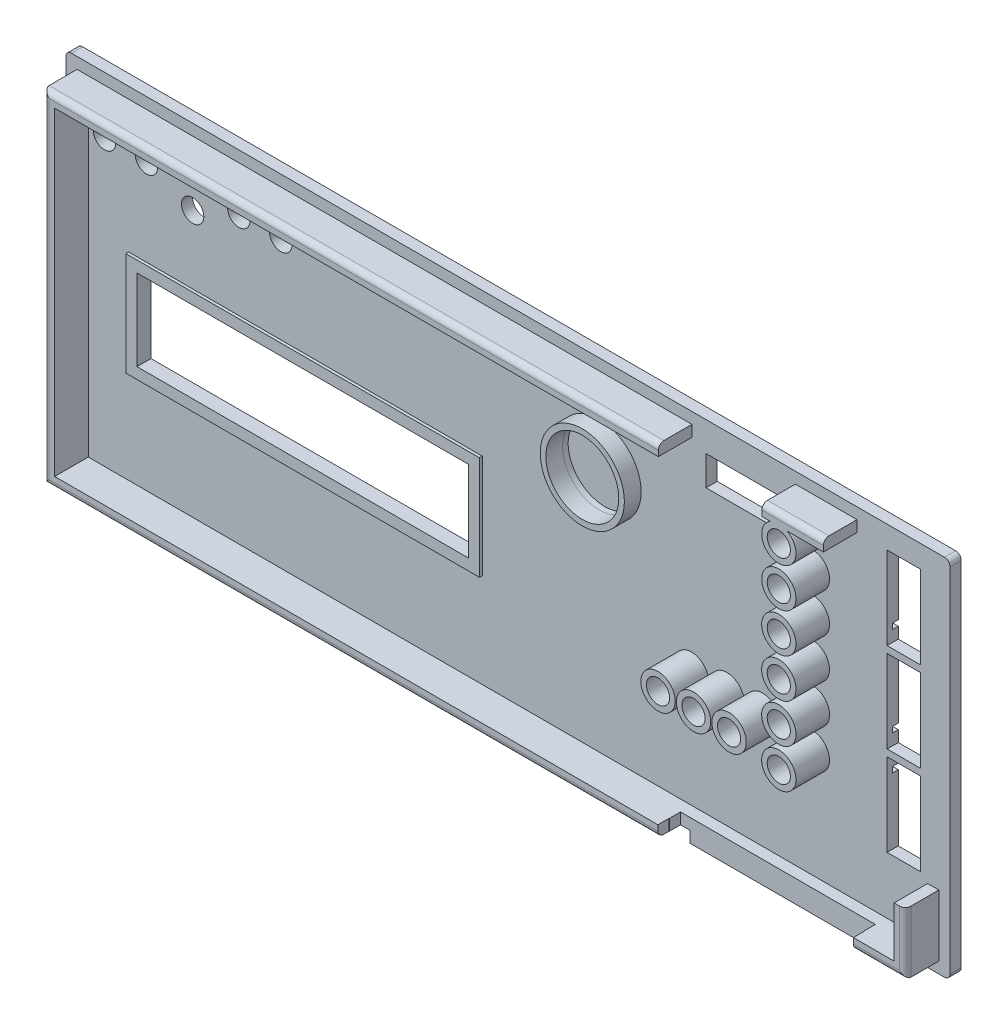
SolidWorks part; units mm, degrees
material "ABS"
ref_plane "Plano frontal" through (0, 0, 0) normal (0, 0, 1) x (1, 0, 0)
ref_plane "Plano superior" through (0, 0, 0) normal (0, 1, 0) x (1, 0, 0)
ref_plane "Plano direito" through (0, 0, 0) normal (1, 0, 0) x (0, 0, -1)
sketch "Esboço1" plane through (0, 0, 0) normal (0, 0, 1) x (1, 0, 0)
  line L1 (0, 0) -> (-158, 0)
  line L2 (0, 0) -> (0, 65)
  line L3 (0, 65) -> (-158, 65)
  line L4 (-158, 0) -> (-158, 65)
  dimension "D1" = 158
  dimension "D2" = 65
extrude "Ressalto-extrusão1" add sketch "Esboço1" along normal blind 2
sketch "Esboço3" [suppressed] plane through (0, 0, 0) normal (0, -1, 0) x (-1, 0, 0)
  line L0 (14.5726, -4) -> (14.5726, -2)
  line L1 (158, -2) -> (0, -2) construction
  line L2 (14.5726, -2) -> (44.0726, -2)
  line L3 (44.0726, -2) -> (44.0726, -4)
  line L4 (44.0726, -4) -> (44.0726, -7.5976)
  line L5 (40.5726, -7.0976) -> (40.5726, -7.5976)
  line L6 (40.5726, -7.0976) -> (40.5726, -8.82) construction
  line L7 (40.5726, -7.5976) -> (41.0832, -7.5976)
  line L8 (43.5621, -7.5976) -> (44.0726, -7.5976)
  line L9 (40.5726, -7.0976) -> (38.2226, -7.0976)
  line L10 (38.2226, -7.0976) -> (38.2226, -6.57)
  line L11 (20.4226, -7.0904) -> (18.0726, -7.0904)
  line L12 (18.0726, -7.0904) -> (18.0726, -7.8318)
  line L13 (36.3225, -4.67) -> (22.3225, -4.6704)
  line L14 (20.4226, -6.5705) -> (20.4226, -7.0904)
  line L15 (18.0726, -8.82) -> (18.0726, -7.0904) construction
  line L16 (18.0726, -7.8318) -> (17.7669, -7.8318)
  line L17 (14.5726, -4) -> (14.5726, -8.82) construction
  line L18 (14.5726, -7.8318) -> (14.5726, -4)
  line L19 (14.8783, -7.8318) -> (14.5726, -7.8318)
  arc A0 (17.7669, -7.8318) -> (14.8783, -7.8318) centre (16.3226, -8.82) ccw
  arc A3 (43.5621, -7.5976) -> (41.0832, -7.5976) centre (42.3226, -8.833) ccw
  arc A5 (38.2226, -6.57) -> (36.3225, -4.67) centre (36.3226, -6.57) ccw
  arc A6 (22.3225, -4.6704) -> (20.4226, -6.5705) centre (22.3226, -6.5704) ccw
  dimension "D1" = 0.5
sketch "Esboço4" plane through (0, 0, 2) normal (0, 0, 1) x (1, 0, 0)
  line L0 (-156, 2) -> (-2, 2)
  line L1 (-2, 2) -> (-2, 63)
  line L2 (-2, 63) -> (-156, 63)
  line L3 (-156, 63) -> (-156, 2)
  line L4 (-154, 4) -> (-4, 4)
  line L5 (-4, 4) -> (-4, 61)
  line L6 (-4, 61) -> (-154, 61)
  line L7 (-154, 61) -> (-154, 4)
  dimension "D1" = 2
extrude "Ressalto-extrusão3" add sketch "Esboço4" along normal blind 6
sketch "Esboço5" plane through (0, 0, 8) normal (0, 0, 1) x (1, 0, 0)
  line L0 (-156, 2) -> (-2, 2) construction
  line L1 (-46.2005, 2) -> (-11.2842, 2)
  line L2 (-46.2005, 2) -> (-46.2005, 4)
  line L3 (-46.2005, 4) -> (-11.2842, 4)
  line L4 (-11.2842, 2) -> (-11.2842, 4)
  line L5 (-154, 4) -> (-4, 4) construction
extrude "Corte-extrusão1" cut sketch "Esboço5" against normal blind 2
sketch "Esboço6" plane through (0, 0, 0) normal (0, 0, -1) x (-1, 0, 0)
  line L1 (11.25, 61) -> (5.25, 61)
  line L2 (11.25, 61) -> (11.25, 46.2)
  line L3 (11.25, 46.2) -> (5.25, 46.2)
  line L4 (5.25, 61) -> (5.25, 46.2)
  line L5 (28.6082, 54.44) -> (43.6082, 54.44)
  line L6 (28.6082, 54.44) -> (28.6082, 59.75)
  line L7 (0, 65) -> (158, 65) construction
  line L8 (0, 0) -> (0, 65) construction
  line L9 (11.25, 45) -> (5.25, 45)
  line L10 (11.25, 45) -> (11.25, 30.2)
  line L11 (11.25, 30.2) -> (5.25, 30.2)
  line L12 (5.25, 45) -> (5.25, 30.2)
  line L13 (11.25, 29) -> (5.25, 29)
  line L14 (11.25, 29) -> (11.25, 14.2)
  line L15 (11.25, 14.2) -> (5.25, 14.2)
  line L16 (5.25, 29) -> (5.25, 14.2)
  line L17 (28.6082, 59.75) -> (43.6082, 59.75)
  line L18 (43.6082, 54.44) -> (43.6082, 59.75)
  dimension "D1" = 6
  dimension "D2" = 4
  dimension "D3" = 14.8
  dimension "D4" = 5.25
  dimension "D6" = 1.2
  dimension "D5" = 3
extrude "Corte-extrusão2" cut sketch "Esboço6" against normal blind 4
fillet "Filete2" radius 1 4 edges at (-158, 0, 1) (-158, 65, 1) (0, 0, 1) (0, 65, 1)
sketch "Esboço7" plane through (0, 0, 0) normal (0, 0, -1) x (-1, 0, 0)
  line L0 (87.0918, 25.05) -> (87.0918, 25.7) construction
  line L1 (85.5918, 22.85) -> (144.7918, 22.85)
  line L2 (85.5918, 22.85) -> (85.5918, 37.35)
  line L3 (85.5918, 37.35) -> (144.7918, 37.35)
  line L4 (144.7918, 22.85) -> (144.7918, 37.35)
  line L5 (95.3418, 24.35) -> (94.7918, 24.35) construction
  line L7 (143.2918, 29.9) -> (143.2918, 29.25) construction
  point P6 (87.0918, 25.375)
  point P9 (95.0668, 24.35)
  dimension "D1" = 14.5
  dimension "D2" = 1.5
  dimension "D3" = 1.5
  dimension "D4" = 1.5
extrude "Corte-extrusão3" cut sketch "Esboço7" against normal blind 2
sketch "Esboço8" plane through (0, 0, 2) normal (0, 0, 1) x (1, 0, 0)
  line L0 (-83.5918, 20.85) -> (-83.5918, 39.35)
  line L1 (-85.5918, 22.85) -> (-144.7918, 22.85)
  line L2 (-85.5918, 22.85) -> (-85.5918, 37.35)
  line L3 (-85.5918, 37.35) -> (-144.7918, 37.35)
  line L4 (-144.7918, 22.85) -> (-144.7918, 37.35)
  line L5 (-83.5918, 39.35) -> (-146.7918, 39.35)
  line L6 (-146.7918, 20.85) -> (-146.7918, 39.35)
  line L7 (-83.5918, 20.85) -> (-146.7918, 20.85)
  dimension "D1" = 2
extrude "Ressalto-extrusão4" add sketch "Esboço8" along normal blind 0.5
sketch "Esboço9" plane through (0, 0, 2) normal (0, 0, 1) x (1, 0, 0)
  line L1 (-1, 65) -> (-157, 65) construction
  line L2 (-158, 64) -> (-158, 1) construction
  circle A0 centre (-119.6, 55) radius 2
  circle A1 centre (-127.1, 55) radius 2
  circle A2 centre (-135.35, 58.5) radius 2
  circle A3 centre (-143.6, 55) radius 2
  circle A4 centre (-135.35, 51.5) radius 2
  circle A5 centre (-151.1, 55) radius 2
  dimension "D1" = 4
  dimension "D2" = 4
  dimension "D3" = 4
  dimension "D4" = 4
  dimension "D5" = 4
  dimension "D6" = 4
  dimension "D7" = 7.5
  dimension "D8" = 7.5
  dimension "D9" = 10
  dimension "D10" = 16.5
  dimension "D11" = 6.9
  dimension "D12" = 7
  dimension "D13" = 3.5
  dimension "D14" = 8.25
sketch "Esboço12" plane through (0, 0, 2) normal (0, 0, 1) x (1, 0, 0)
  circle A0 centre (-46.1882, 24.665) radius 1.87
  circle A1 centre (-39.8382, 24.665) radius 1.87
  circle A2 centre (-33.4882, 24.665) radius 1.87
  circle A3 centre (-24.5982, 23.32) radius 1.87
  circle A4 centre (-24.5982, 30.32) radius 1.87
  circle A5 centre (-24.5982, 37.32) radius 1.87
  circle A6 centre (-24.5982, 44.32) radius 1.87
  circle A7 centre (-24.5982, 51.32) radius 1.87
  circle A8 centre (-24.5982, 58.32) radius 1.87
  circle A9 centre (-46.1882, 24.665) radius 2.07
  circle A10 centre (-39.8382, 24.665) radius 2.07
  circle A11 centre (-33.4882, 24.665) radius 2.07
  circle A12 centre (-24.5982, 23.32) radius 2.07
  circle A13 centre (-24.5982, 30.32) radius 2.07
  circle A14 centre (-24.5982, 37.32) radius 2.07
  circle A15 centre (-24.5982, 44.32) radius 2.07
  circle A16 centre (-24.5982, 51.32) radius 2.07
  circle A17 centre (-24.5982, 58.32) radius 2.07
  circle A18 centre (-24.5982, 23.32) radius 3.07
  circle A19 centre (-33.4882, 24.665) radius 3.07
  circle A20 centre (-39.8382, 24.665) radius 3.07
  circle A21 centre (-46.1882, 24.665) radius 3.07
  circle A22 centre (-24.5982, 30.32) radius 3.07
  circle A23 centre (-24.5982, 37.32) radius 3.07
  circle A24 centre (-24.5982, 44.32) radius 3.07
  circle A25 centre (-24.5982, 51.32) radius 3.07
  circle A26 centre (-24.5982, 58.32) radius 3.07
  dimension "D3" = 7
  dimension "D1" = 7
  dimension "D2" = 1
extrude "Ressalto-extrusão7" add sketch "Esboço12" along normal blind 6
sketch "Esboço13" plane through (0, 0, 2) normal (0, 0, 1) x (1, 0, 0)
  circle A1 centre (-24.5982, 58.32) radius 2.07
  circle A2 centre (-24.5982, 58.32) radius 2.07
  circle A3 centre (-24.5982, 51.32) radius 2.07
  circle A4 centre (-24.5982, 51.32) radius 2.07
  circle A5 centre (-24.5982, 44.32) radius 2.07
  circle A6 centre (-24.5982, 44.32) radius 2.07
  circle A7 centre (-24.5982, 37.32) radius 2.07
  circle A8 centre (-24.5982, 37.32) radius 2.07
  circle A9 centre (-24.5982, 30.32) radius 2.07
  circle A10 centre (-24.5982, 30.32) radius 2.07
  circle A11 centre (-24.5982, 23.32) radius 2.07
  circle A12 centre (-24.5982, 23.32) radius 2.07
  circle A13 centre (-33.4882, 24.665) radius 2.07
  circle A14 centre (-33.4882, 24.665) radius 2.07
  circle A15 centre (-39.8382, 24.665) radius 2.07
  circle A16 centre (-39.8382, 24.665) radius 2.07
  circle A17 centre (-46.1882, 24.665) radius 2.07
  circle A18 centre (-46.1882, 24.665) radius 2.07
  dimension "D1" = 0
  dimension "D2" = 0
  dimension "D3" = 0
  dimension "D4" = 0
  dimension "D5" = 0
  dimension "D6" = 0
  dimension "D7" = 0
  dimension "D8" = 0
  dimension "D9" = 0
extrude "Corte-extrusão7" cut sketch "Esboço13" against normal blind 1.5
fillet "Filete8" radius 1 9 edges at (-44.1182, 24.665, 0.5) (-22.5282, 58.32, 0.5) (-22.5282, 51.32, 0.5) (-22.5282, 44.32, 0.5) (-22.5282, 37.32, 0.5) (-22.5282, 30.32, 0.5) (-22.5282, 23.32, 0.5) (-31.4182, 24.665, 0.5) (-37.7682, 24.665, 0.5)
sketch "Esboço15" plane through (0, 0, 2) normal (0, 0, 1) x (1, 0, 0)
  circle A0 centre (-62.7168, 48.007) radius 6.5216
  circle A1 centre (-62.7168, 48.007) radius 7.5216
  dimension "D1" = 1
extrude "Ressalto-extrusão15" add sketch "Esboço15" along normal blind 3 separate body
sketch "Esboço16" plane through (0, 0, 2) normal (0, 0, 1) x (1, 0, 0)
  circle A0 centre (-62.7168, 48.007) radius 6.5216
  circle A1 centre (-62.7168, 48.007) radius 6.5216 construction
fillet "Filete9" radius 1 5 edges at (-101.1002, 2, 8) (-156, 32.5, 8) (-79, 63, 8) (-2, 32.5, 8) (-6.6421, 2, 8)
sketch "Esboço18" plane through (0, 0, 2) normal (0, 0, 1) x (1, 0, 0)
  line L1 (-1.7179, 13.0006) -> (-16.6289, 13.0006)
  line L2 (-1.7179, 13.0006) -> (-1.7179, 63.3344)
  line L3 (-1.7179, 63.3344) -> (-16.6289, 63.3344)
  line L4 (-16.6289, 13.0006) -> (-16.6289, 63.3344)
  line L7 (-11.3413, 11.3001) -> (-46.1715, 11.3001)
  line L8 (-11.3413, 11.3001) -> (-11.3413, 1.1781)
  line L9 (-11.3413, 1.1781) -> (-46.1715, 1.1781)
  line L10 (-46.1715, 11.3001) -> (-46.1715, 1.1781)
  line L11 (-46.1248, 64.7569) -> (-27.6214, 64.7569)
  line L12 (-46.1248, 64.7569) -> (-46.1248, 50.7859)
  line L13 (-46.1248, 50.7859) -> (-27.6214, 50.7859)
  line L14 (-27.6214, 64.7569) -> (-27.6214, 50.7859)
  circle A0 centre (-24.5982, 51.32) radius 3.07 construction
extrude "Corte-extrusão11" cut sketch "Esboço18" along normal blind 12
extrude "Corte-extrusão12" cut sketch "Esboço16" against normal blind 1
extrude "Corte-extrusão13" cut sketch "Esboço9" against normal blind 4
sketch "Esboço19" plane through (0, 0, 2) normal (0, 0, 1) x (1, 0, 0)
  line L1 (-46.1715, 4) -> (-11.3413, 4)
  line L2 (-46.1715, 4) -> (-46.1715, 2)
  line L3 (-46.1715, 2) -> (-11.3413, 2)
  line L4 (-11.3413, 4) -> (-11.3413, 2)
extrude "Ressalto-extrusão16" add sketch "Esboço19" along normal blind 2
sketch "Esboço20" plane through (0, 0, 0) normal (0, 0, -1) x (-1, 0, 0)
  line L0 (11.25, 33.2) -> (17.1926, 33.2)
  line L1 (17.1926, 33.2) -> (17.1926, 37.1)
  line L2 (17.1926, 37.1) -> (16.2335, 37.1)
  line L3 (16.2335, 37.1) -> (13.5902, 35.6872)
  line L4 (11.25, 30.2) -> (11.25, 45) construction
  line L5 (17.1926, 37.1) -> (17.1926, 42)
  line L6 (17.1926, 42) -> (16.2335, 42)
  line L7 (16.2335, 42) -> (13.5902, 40.5872)
  line L8 (5.25, 30.2) -> (11.25, 30.2) construction
  line L9 (11.25, 32.2) -> (18.1926, 32.2)
  line L10 (18.1926, 32.2) -> (18.1926, 37.1)
  line L11 (18.1926, 37.1) -> (18.1926, 43)
  line L12 (18.1926, 43) -> (15.983, 43)
  line L13 (15.983, 43) -> (13.1188, 41.4691)
  line L14 (17.1926, 38.1) -> (15.983, 38.1)
  line L15 (15.983, 38.1) -> (13.1188, 36.5691)
  line L16 (11.25, 45) -> (5.25, 45) construction
  line L17 (11.2478, 49.2) -> (17.1904, 49.2)
  line L18 (13.1188, 36.5691) -> (13.5902, 35.6872)
  line L19 (17.1904, 49.2) -> (17.1904, 53.1)
  line L20 (17.1904, 53.1) -> (16.2312, 53.1)
  line L21 (13.5902, 40.5872) -> (13.1188, 41.4691)
  line L22 (16.2312, 53.1) -> (13.5879, 51.6872)
  line L23 (17.1904, 53.1) -> (17.1904, 58)
  line L24 (11.25, 32.2) -> (11.25, 33.2)
  line L25 (17.1904, 58) -> (16.2312, 58)
  line L26 (16.2312, 58) -> (13.5879, 56.5872)
  line L27 (11.2478, 48.2) -> (18.1904, 48.2)
  line L28 (18.1904, 48.2) -> (18.1904, 53.1)
  line L29 (18.1904, 53.1) -> (18.1904, 59)
  line L30 (18.1904, 59) -> (15.9808, 59)
  line L31 (15.9808, 59) -> (13.1165, 57.4691)
  line L32 (17.1904, 54.1) -> (15.9808, 54.1)
  line L33 (15.9808, 54.1) -> (13.1165, 52.5691)
  line L34 (13.1165, 52.5691) -> (13.5879, 51.6872)
  line L35 (13.5879, 56.5872) -> (13.1165, 57.4691)
  line L36 (11.2478, 48.2) -> (11.2478, 49.2)
  line L37 (5.25, 46.2) -> (11.25, 46.2) construction
  line L38 (11.25, 61) -> (5.25, 61) construction
  line L39 (17.1936, 16.2) -> (16.2344, 16.2)
  line L40 (17.1936, 17.2) -> (17.1936, 21.1)
  line L41 (17.1936, 21.1) -> (16.2344, 21.1)
  line L42 (16.2344, 21.1) -> (13.5911, 19.6872)
  line L43 (17.1936, 21.1) -> (17.1936, 26)
  line L44 (17.1936, 26) -> (11.25, 26)
  line L45 (18.1936, 27) -> (11.25, 27)
  line L46 (16.2344, 16.2) -> (13.5911, 14.7872)
  line L47 (18.1936, 16.2) -> (18.1936, 21.1)
  line L48 (18.1936, 21.1) -> (18.1936, 27)
  line L49 (11.25, 14.2) -> (11.25, 29) construction
  line L50 (11.25, 27) -> (11.25, 26)
  line L51 (17.1936, 22.1) -> (15.9839, 22.1)
  line L52 (15.9839, 22.1) -> (13.1197, 20.5691)
  line L53 (13.1197, 20.5691) -> (13.5911, 19.6872)
  line L54 (17.1936, 17.2) -> (15.9839, 17.2)
  line L55 (15.9839, 17.2) -> (13.1197, 15.6691)
  line L56 (13.1197, 15.6691) -> (13.5911, 14.7872)
  line L57 (17.1936, 16.2) -> (18.1936, 16.2)
  line L58 (11.25, 29) -> (5.25, 29) construction
  line L59 (5.25, 14.2) -> (11.25, 14.2) construction
  point P27 (16.714, 16.2)
  point P30 (17.0878, 43)
  dimension "D1" = 1
  dimension "D2" = 2
  dimension "D3" = 2
  dimension "D4" = 3.9
  dimension "D5" = 3.9
  dimension "D6" = 2
  dimension "D7" = 1
  dimension "D8" = 2
  dimension "D9" = 1
  dimension "D10" = 2
  dimension "D11" = 1
  dimension "D12" = 2
  dimension "D13" = 1
  dimension "D14" = 3.9
  dimension "D15" = 1
extrude "Corte-extrusão14" cut sketch "Esboço20" against normal blind 1
sketch "Esboço21" plane through (0, 0, 0) normal (0, 0, -1) x (-1, 0, 0)
  line L0 (28.6082, 59.75) -> (28.6082, 54.44) construction
  line L1 (34.6082, 48.44) -> (28.6082, 48.44)
  line L2 (34.6082, 48.44) -> (34.6082, 49.44)
  line L3 (34.6082, 49.44) -> (28.6082, 49.44)
  line L4 (28.6082, 48.44) -> (28.6082, 49.44)
  line L5 (33.6082, 50.44) -> (29.6082, 50.44)
  line L6 (33.6082, 50.44) -> (33.6082, 51.44)
  line L7 (33.6082, 51.44) -> (29.6082, 51.44)
  line L8 (29.6082, 50.44) -> (29.6082, 51.44)
  line L9 (32.6082, 52.44) -> (30.6082, 52.44)
  line L10 (32.6082, 52.44) -> (32.6082, 53.44)
  line L11 (32.6082, 53.44) -> (30.6082, 53.44)
  line L12 (30.6082, 52.44) -> (30.6082, 53.44)
  line L13 (31.1082, 48.44) -> (32.1082, 48.44)
  line L14 (31.1082, 48.44) -> (31.1082, 45.44)
  line L15 (31.1082, 45.44) -> (32.1082, 45.44)
  line L16 (32.1082, 48.44) -> (32.1082, 45.44)
  line L17 (28.6082, 54.44) -> (43.6082, 54.44) construction
  point P16 (31.6082, 48.44)
  dimension "D1" = 1
  dimension "D2" = 1
  dimension "D3" = 1
  dimension "D4" = 1
  dimension "D5" = 1
  dimension "D6" = 1
  dimension "D7" = 1
  dimension "D8" = 1
  dimension "D9" = 1
  dimension "D10" = 6
  dimension "D11" = 3
  dimension "D12" = 0.5
  dimension "D13" = 0.5
  dimension "D14" = 1
extrude "Corte-extrusão15" cut sketch "Esboço21" against normal blind 1 contours L16 L1 L14 L15 | L4 L1 L2 L3 | L8 L5 L6 L7 | L12 L9 L10 L11
sketch "Esboço22" plane through (0, 0, 0) normal (0, 0, -1) x (-1, 0, 0)
  text T0 "8  9" font "Century Gothic" height 3.5
extrude "Corte-extrusão17" cut sketch "Esboço22" against normal blind 1
sketch "Esboço23" plane through (0, 2, 0) normal (0, -1, 0) x (-1, 0, 0)
  line L0 (46.1715, -4) -> (11.3413, -4) construction
  line L1 (12.5, -4) -> (44.5, -4)
  line L2 (12.5, -4) -> (12.5, -2)
  line L3 (12.5, -2) -> (44.5, -2)
  line L4 (44.5, -4) -> (44.5, -2)
  line L5 (157, -2) -> (1, -2) construction
  line L6 (12, -2) -> (12, -20) construction
  line L7 (45, -2) -> (45, -20) construction
  dimension "D1" = 0.5
  dimension "D2" = 0.5
extrude "Ressalto-extrusão17" add sketch "Esboço23" along normal blind 2
